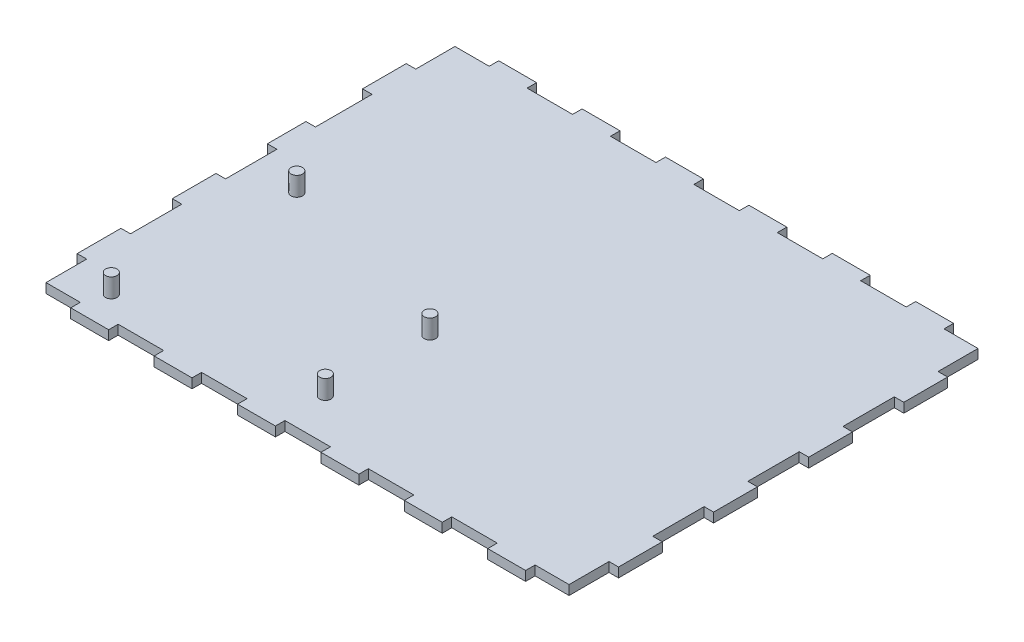
SolidWorks part; units mm, degrees
ref_plane "Front Plane" through (0, 0, 0) normal (0, 0, 1) x (1, 0, 0)
ref_plane "Top Plane" through (0, 0, 0) normal (0, 1, 0) x (1, 0, 0)
ref_plane "Right Plane" through (0, 0, 0) normal (1, 0, 0) x (0, 0, -1)
sketch "Sketch1" plane through (0, 0, 0) normal (0, 1, 0) x (1, 0, 0)
  line L1 (-72.39, 57.15) -> (72.39, 57.15)
  line L2 (-72.39, 57.15) -> (-72.39, -57.15)
  line L3 (-72.39, -57.15) -> (72.39, -57.15)
  line L4 (72.39, 57.15) -> (72.39, -57.15)
  line L5 (-72.39, 57.15) -> (72.39, -57.15) construction
  line L6 (-72.39, -57.15) -> (72.39, 57.15) construction
  point P0 (0, 0)
  dimension "D1" = 144.78
  dimension "D2" = 114.3
extrude "Boss-Extrude1" add sketch "Sketch1" along normal blind 63.5
sketch "Sketch2" plane through (0, 63.5, 0) normal (0, 1, 0) x (1, 0, 0)
  line L1 (-72.39, 57.15) -> (72.39, 57.15)
  line L2 (-72.39, 57.15) -> (-72.39, -57.15)
  line L3 (-72.39, -57.15) -> (72.39, -57.15)
  line L4 (72.39, 57.15) -> (72.39, -57.15)
  line L5 (-72.39, 57.15) -> (72.39, -57.15) construction
  line L6 (-72.39, -57.15) -> (72.39, 57.15) construction
  point P0 (0, 0)
extrude "Cut-Extrude1" cut sketch "Sketch2" against normal blind 60.96
sketch "Sketch3" plane through (0, 2.54, 0) normal (0, 1, 0) x (1, 0, 0)
  line L0 (-72.39, 57.15) -> (-72.39, -57.15) construction
  line L1 (-72.39, 2.2148) -> (-3.81, 2.2148) construction
  line L2 (-72.39, 2.2148) -> (-72.39, -51.1252) construction
  line L3 (-72.39, -51.1252) -> (-3.81, -51.1252) construction
  line L4 (-3.81, 2.2148) -> (-3.81, -51.1252) construction
  line L5 (-72.39, 2.2148) -> (-3.81, -51.1252) construction
  line L6 (-72.39, -51.1252) -> (-3.81, 2.2148) construction
  line L7 (-72.39, -57.15) -> (72.39, -57.15) construction
  circle A0 centre (-58.42, -48.5852) radius 1.524
  circle A1 centre (-6.35, -43.5052) radius 1.524
  circle A2 centre (-6.35, -15.5652) radius 1.524
  circle A3 centre (-57.15, -0.3252) radius 1.524
  point P0 (-3.6659, -1.4511)
  dimension "D10" = 3.048
  dimension "D1" = 68.58
  dimension "D2" = 53.34
  dimension "D3" = 2.54
  dimension "D4" = 5.08
  dimension "D5" = 27.94
  dimension "D6" = 15.24
  dimension "D7" = 1.27
  dimension "D8" = 13.97
  dimension "D9" = 50.8
  dimension "D11" = 6.0248
extrude "Boss-Extrude2" add sketch "Sketch3" along normal blind 5.08
sketch "Sketch4" plane through (0, 2.54, 0) normal (0, 1, 0) x (1, 0, 0)
  line L0 (69.85, 54.61) -> (61.2969, 54.61)
  line L1 (61.2969, 54.61) -> (61.2969, 57.15)
  line L2 (61.2969, 57.15) -> (50.16, 57.15)
  line L3 (50.16, 57.15) -> (50.16, 54.61)
  line L4 (50.16, 54.61) -> (39.023, 54.61)
  line L5 (39.023, 54.61) -> (39.023, 57.15)
  line L6 (39.023, 57.15) -> (27.8861, 57.15)
  line L7 (27.8861, 57.15) -> (27.8861, 54.61)
  line L8 (27.8861, 54.61) -> (16.7492, 54.61)
  line L9 (16.7492, 54.61) -> (16.7492, 57.15)
  line L10 (16.7492, 57.15) -> (5.6123, 57.15)
  line L11 (5.6123, 57.15) -> (5.6123, 54.61)
  line L12 (5.6123, 54.61) -> (-5.5247, 54.61)
  line L13 (-5.5247, 54.61) -> (-5.5247, 57.15)
  line L14 (-5.5247, 57.15) -> (-16.6616, 57.15)
  line L15 (-16.6616, 57.15) -> (-16.6616, 54.61)
  line L16 (-16.6616, 54.61) -> (-27.7985, 54.61)
  line L17 (-27.7985, 54.61) -> (-27.7985, 57.15)
  line L18 (-27.7985, 57.15) -> (-38.9354, 57.15)
  line L19 (-38.9354, 57.15) -> (-38.9354, 54.61)
  line L20 (-38.9354, 54.61) -> (-50.0724, 54.61)
  line L21 (-50.0724, 54.61) -> (-50.0724, 57.15)
  line L22 (-50.0724, 57.15) -> (-61.2093, 57.15)
  line L23 (-61.2093, 57.15) -> (-61.2093, 54.61)
  line L24 (-61.2093, 54.61) -> (-69.85, 54.61)
  line L25 (-61.2093, 54.61) -> (-61.2093, -57.15) construction
  line L26 (72.39, 57.15) -> (-72.39, 57.15) construction
  line L52 (-72.39, 57.15) -> (-72.39, -57.15) construction
  line L53 (5.6123, 54.61) -> (5.6123, -57.15) construction
  line L54 (-69.85, 54.61) -> (-69.85, 44.6536)
  line L55 (-69.85, 44.6536) -> (-72.39, 44.6536)
  line L56 (-72.39, 44.6536) -> (-72.39, 31.9536)
  line L57 (-72.39, 31.9536) -> (-69.85, 31.9536)
  line L58 (-69.85, 31.9536) -> (-69.85, 19.2536)
  line L59 (-69.85, 19.2536) -> (-72.39, 19.2536)
  line L60 (-72.39, 19.2536) -> (-72.39, 6.5536)
  line L61 (-72.39, 6.5536) -> (-69.85, 6.5536)
  line L62 (-69.85, 6.5536) -> (-69.85, -6.1464)
  line L63 (-69.85, -6.1464) -> (-72.39, -6.1464)
  line L64 (-72.39, -6.1464) -> (-72.39, -18.8464)
  line L65 (-72.39, -18.8464) -> (-69.85, -18.8464)
  line L66 (-69.85, -18.8464) -> (-69.85, -31.5464)
  line L67 (-69.85, -31.5464) -> (-72.39, -31.5464)
  line L68 (-72.39, -31.5464) -> (-72.39, -44.2464)
  line L69 (-72.39, -44.2464) -> (-69.85, -44.2464)
  line L70 (-69.85, -44.2464) -> (-69.85, -54.61)
  line L71 (69.85, 54.61) -> (69.85, 44.45)
  line L72 (69.85, 44.45) -> (72.39, 44.45)
  line L73 (72.39, 44.45) -> (72.39, 31.75)
  line L74 (72.39, 31.75) -> (69.85, 31.75)
  line L75 (69.85, 31.75) -> (69.85, 19.05)
  line L76 (69.85, 19.05) -> (72.39, 19.05)
  line L77 (72.39, 19.05) -> (72.39, 6.35)
  line L78 (72.39, 6.35) -> (69.85, 6.35)
  line L79 (69.85, 6.35) -> (69.85, -6.35)
  line L80 (69.85, -6.35) -> (72.39, -6.35)
  line L81 (72.39, -6.35) -> (72.39, -19.05)
  line L82 (72.39, -19.05) -> (69.85, -19.05)
  line L83 (69.85, -19.05) -> (69.85, -31.75)
  line L84 (69.85, -31.75) -> (72.39, -31.75)
  line L85 (72.39, -31.75) -> (72.39, -44.45)
  line L86 (72.39, -44.45) -> (69.85, -44.45)
  line L87 (69.85, -44.45) -> (69.85, -54.61)
  line L88 (61.2969, 54.61) -> (61.2969, -57.15) construction
  line L89 (72.39, -57.15) -> (72.39, 57.15) construction
  line L90 (-50.0724, 54.61) -> (-50.0724, -57.15) construction
  line L91 (-72.39, -57.15) -> (72.39, -57.15) construction
  line L92 (-38.9354, 54.61) -> (-38.9354, -57.15) construction
  line L93 (-27.7985, 54.61) -> (-27.7985, -57.15) construction
  line L94 (-16.6616, 54.61) -> (-16.6616, -57.15) construction
  line L95 (-5.5247, 54.61) -> (-5.5247, -57.15) construction
  line L96 (16.7492, 54.61) -> (16.7492, -57.15) construction
  line L97 (27.8861, 54.61) -> (27.8861, -57.15) construction
  line L98 (39.023, 54.61) -> (39.023, -57.15) construction
  line L99 (50.16, 54.61) -> (50.16, -57.15) construction
  line L100 (-69.85, -54.61) -> (-61.2093, -54.61)
  line L101 (-61.2093, -54.61) -> (-61.2093, -57.15)
  line L102 (-50.0724, -57.15) -> (-50.0724, -54.61)
  line L103 (-50.0724, -54.61) -> (-38.9354, -54.61)
  line L104 (-38.9354, -54.61) -> (-38.9354, -57.15)
  line L105 (-27.7985, -57.15) -> (-27.7985, -54.61)
  line L106 (-27.7985, -54.61) -> (-16.6616, -54.61)
  line L107 (-16.6616, -54.61) -> (-16.6616, -57.15)
  line L108 (-5.5247, -57.15) -> (-5.5247, -54.61)
  line L109 (-5.5247, -54.61) -> (5.6123, -54.61)
  line L110 (5.6123, -54.61) -> (5.6123, -57.15)
  line L111 (16.7492, -57.15) -> (16.7492, -54.61)
  line L112 (16.7492, -54.61) -> (27.8861, -54.61)
  line L113 (27.8861, -54.61) -> (27.8861, -57.15)
  line L114 (39.023, -57.15) -> (39.023, -54.61)
  line L115 (39.023, -54.61) -> (50.16, -54.61)
  line L116 (50.16, -54.61) -> (50.16, -57.15)
  line L117 (61.2969, -57.15) -> (61.2969, -54.61)
  line L118 (61.2969, -54.61) -> (69.85, -54.61)
  line L119 (-61.2093, -57.15) -> (-50.0724, -57.15)
  line L120 (-38.9354, -57.15) -> (-27.7985, -57.15)
  line L121 (-16.6616, -57.15) -> (-5.5247, -57.15)
  line L122 (5.6123, -57.15) -> (16.7492, -57.15)
  line L123 (27.8861, -57.15) -> (39.023, -57.15)
  line L124 (61.2969, -57.15) -> (50.16, -57.15)
  dimension "D1" = 2.54
  dimension "D3" = 2.54
  dimension "D4" = 2.54
extrude "Cut-Extrude2" cut sketch "Sketch4" against normal blind 2.54 flip side to cut
sketch "Sketch6" plane through (0, 2.54, 0) normal (0, 1, 0) x (1, 0, 0)
  line L0 (-69.85, 54.61) -> (-60.7013, 54.61)
  line L2 (-60.7013, 54.61) -> (-60.7013, 57.15)
  line L3 (-50.0724, 57.15) -> (-61.2093, 57.15) construction
  line L4 (-69.85, 54.61) -> (-69.85, 44.1456)
  line L5 (-69.85, 44.1456) -> (-72.39, 44.1456)
  line L6 (-72.39, 44.6536) -> (-72.39, 31.9536) construction
  line L7 (-72.39, 44.1456) -> (-72.39, 32.4616)
  line L8 (-72.39, 32.4616) -> (-69.85, 32.4616)
  line L9 (-69.85, 32.4616) -> (-69.85, 17.3578)
  line L10 (-69.85, 17.3578) -> (-72.39, 17.3578)
  line L11 (-72.39, 19.2536) -> (-72.39, 6.5536) construction
  line L12 (-72.39, 17.3578) -> (-72.39, 7.0616)
  line L13 (-72.39, 7.0616) -> (-69.85, 7.0616)
  line L14 (-69.85, 7.0616) -> (-69.85, -6.6544)
  line L15 (-69.85, -6.6544) -> (-72.39, -6.6544)
  line L16 (-72.39, -6.1464) -> (-72.39, -18.8464) construction
  line L17 (-72.39, -6.6544) -> (-72.39, -18.3384)
  line L18 (-72.39, -18.3384) -> (-69.85, -18.3384)
  line L19 (-69.85, -18.3384) -> (-69.85, -32.0544)
  line L20 (-69.85, -32.0544) -> (-72.39, -32.0544)
  line L21 (-72.39, -31.5464) -> (-72.39, -44.2464) construction
  line L22 (-72.39, -32.0544) -> (-72.39, -43.7384)
  line L23 (-72.39, -43.7384) -> (-69.85, -43.7384)
  line L24 (-69.85, -43.7384) -> (-69.85, -54.61)
  line L25 (-69.85, -44.2464) -> (-69.85, -54.61) construction
  line L27 (-72.39, 44.6536) -> (-72.39, 44.1456) construction
  line L28 (-72.39, 31.9536) -> (-72.39, 32.4616) construction
  line L29 (-72.39, 17.3578) -> (-72.39, 17.8658) construction
  line L30 (-72.39, 7.0616) -> (-72.39, 6.5536) construction
  line L31 (-72.39, -6.1464) -> (-72.39, -6.6544) construction
  line L32 (-72.39, -18.8464) -> (-72.39, -18.3384) construction
  line L33 (-72.39, -18.8464) -> (-69.85, -18.8464) construction
  line L34 (-72.39, -32.0544) -> (-72.39, -31.5464) construction
  line L35 (-72.39, -44.2464) -> (-72.39, -43.7384) construction
  line L36 (-60.7013, 57.15) -> (-50.5804, 57.15)
  line L37 (-50.5804, 57.15) -> (-50.5804, 54.61)
  line L38 (-50.5804, 54.61) -> (-38.4274, 54.61)
  line L39 (-38.4274, 54.61) -> (-38.4274, 57.15)
  line L40 (-27.7985, 57.15) -> (-38.9354, 57.15) construction
  line L41 (-38.4274, 57.15) -> (-28.3065, 57.15)
  line L42 (-28.3065, 57.15) -> (-28.3065, 54.61)
  line L43 (-28.3065, 54.61) -> (-16.1536, 54.61)
  line L44 (-16.1536, 54.61) -> (-16.1536, 57.15)
  line L45 (-5.5247, 57.15) -> (-16.6616, 57.15) construction
  line L46 (-16.1536, 57.15) -> (-6.0327, 57.15)
  line L47 (-6.0327, 57.15) -> (-6.0327, 54.61)
  line L48 (-6.0327, 54.61) -> (6.1203, 54.61)
  line L49 (6.1203, 54.61) -> (6.1203, 57.15)
  line L50 (6.1203, 57.15) -> (16.2412, 57.15)
  line L51 (16.7492, 57.15) -> (5.6123, 57.15) construction
  line L52 (16.2412, 57.15) -> (16.2412, 54.61)
  line L53 (16.2412, 54.61) -> (28.3941, 54.61)
  line L54 (28.3941, 54.61) -> (28.3941, 57.15)
  line L55 (39.023, 57.15) -> (27.8861, 57.15) construction
  line L56 (28.3941, 57.15) -> (38.515, 57.15)
  line L57 (38.515, 57.15) -> (38.515, 54.61)
  line L58 (38.515, 54.61) -> (50.668, 54.61)
  line L59 (50.668, 54.61) -> (50.668, 57.15)
  line L60 (61.2969, 57.15) -> (50.16, 57.15) construction
  line L61 (50.668, 57.15) -> (60.7889, 57.15)
  line L62 (60.7889, 57.15) -> (60.7889, 54.61)
  line L63 (60.7889, 54.61) -> (69.85, 54.61)
  line L64 (69.85, 54.61) -> (69.85, 43.942)
  line L65 (69.85, 43.942) -> (72.39, 43.942)
  line L66 (72.39, 31.75) -> (72.39, 44.45) construction
  line L67 (72.39, 43.942) -> (72.39, 32.258)
  line L68 (72.39, 32.258) -> (69.85, 32.258)
  line L69 (69.85, 32.258) -> (69.85, 18.542)
  line L70 (69.85, 18.542) -> (72.39, 18.542)
  line L71 (72.39, 6.35) -> (72.39, 19.05) construction
  line L72 (72.39, 18.542) -> (72.39, 6.858)
  line L73 (72.39, 6.858) -> (69.85, 6.858)
  line L74 (69.85, 6.858) -> (69.85, -6.858)
  line L75 (69.85, -6.858) -> (72.39, -6.858)
  line L76 (72.39, -19.05) -> (72.39, -6.35) construction
  line L77 (72.39, -6.858) -> (72.39, -18.542)
  line L78 (72.39, -18.542) -> (69.85, -18.542)
  line L79 (69.85, -18.542) -> (69.85, -32.258)
  line L80 (69.85, -32.258) -> (72.39, -32.258)
  line L81 (72.39, -44.45) -> (72.39, -31.75) construction
  line L82 (72.39, -32.258) -> (72.39, -43.942)
  line L83 (72.39, -43.942) -> (69.85, -43.942)
  line L84 (69.85, -43.942) -> (69.85, -54.61)
  line L85 (69.85, -54.61) -> (60.7889, -54.61)
  line L86 (60.7889, -54.61) -> (60.7889, -57.15)
  line L87 (50.16, -57.15) -> (61.2969, -57.15) construction
  line L88 (60.7889, -57.15) -> (50.668, -57.15)
  line L89 (50.668, -57.15) -> (50.668, -54.61)
  line L90 (50.668, -54.61) -> (38.515, -54.61)
  line L91 (38.515, -54.61) -> (38.515, -57.15)
  line L92 (27.8861, -57.15) -> (39.023, -57.15) construction
  line L93 (38.515, -57.15) -> (28.3941, -57.15)
  line L94 (28.3941, -57.15) -> (28.3941, -54.61)
  line L95 (28.3941, -54.61) -> (16.2412, -54.61)
  line L96 (16.2412, -54.61) -> (16.2412, -57.15)
  line L97 (5.6123, -57.15) -> (16.7492, -57.15) construction
  line L98 (16.2412, -57.15) -> (6.1203, -57.15)
  line L99 (6.1203, -57.15) -> (6.1203, -54.61)
  line L100 (6.1203, -54.61) -> (-6.0327, -54.61)
  line L101 (-6.0327, -54.61) -> (-6.0327, -57.15)
  line L102 (-16.6616, -57.15) -> (-5.5247, -57.15) construction
  line L103 (-6.0327, -57.15) -> (-16.1536, -57.15)
  line L104 (-16.1536, -57.15) -> (-16.1536, -54.61)
  line L105 (-16.1536, -54.61) -> (-28.3065, -54.61)
  line L106 (-28.3065, -54.61) -> (-28.3065, -57.15)
  line L107 (-38.9354, -57.15) -> (-27.7985, -57.15) construction
  line L108 (-28.3065, -57.15) -> (-38.4274, -57.15)
  line L109 (-38.4274, -57.15) -> (-38.4274, -54.61)
  line L110 (-38.4274, -54.61) -> (-50.5804, -54.61)
  line L111 (-50.5804, -54.61) -> (-50.5804, -57.15)
  line L112 (-61.2093, -57.15) -> (-50.0724, -57.15) construction
  line L113 (-50.5804, -57.15) -> (-60.7013, -57.15)
  line L114 (-60.7013, -57.15) -> (-60.7013, -54.61)
  line L115 (-60.7013, -54.61) -> (-69.85, -54.61)
  line L116 (-61.2093, -57.15) -> (-60.7013, -57.15) construction
  line L117 (-50.0724, -57.15) -> (-50.5804, -57.15) construction
  line L118 (-38.9354, -57.15) -> (-38.4274, -57.15) construction
  line L119 (-27.7985, -57.15) -> (-28.3065, -57.15) construction
  line L120 (-16.6616, -57.15) -> (-16.1536, -57.15) construction
  line L121 (-5.5247, -57.15) -> (-6.0327, -57.15) construction
  line L122 (5.6123, -57.15) -> (6.1203, -57.15) construction
  line L123 (16.7492, -57.15) -> (16.2412, -57.15) construction
  line L124 (27.8861, -57.15) -> (28.3941, -57.15) construction
  line L125 (39.023, -57.15) -> (38.515, -57.15) construction
  line L126 (50.16, -57.15) -> (50.668, -57.15) construction
  line L127 (61.2969, -57.15) -> (60.7889, -57.15) construction
  line L128 (72.39, -44.45) -> (72.39, -43.942) construction
  line L129 (72.39, -31.75) -> (72.39, -32.258) construction
  line L130 (72.39, -19.05) -> (72.39, -18.542) construction
  line L131 (72.39, -6.35) -> (72.39, -6.858) construction
  line L132 (72.39, 6.35) -> (72.39, 6.858) construction
  line L133 (72.39, 19.05) -> (72.39, 18.542) construction
  line L134 (72.39, 31.75) -> (72.39, 32.258) construction
  line L135 (72.39, 44.45) -> (72.39, 43.942) construction
  line L136 (61.2969, 57.15) -> (60.7889, 57.15) construction
  line L137 (50.16, 57.15) -> (50.668, 57.15) construction
  line L138 (39.023, 57.15) -> (38.515, 57.15) construction
  line L139 (27.8861, 57.15) -> (28.3941, 57.15) construction
  line L140 (16.7492, 57.15) -> (16.2412, 57.15) construction
  line L141 (5.6123, 57.15) -> (6.1203, 57.15) construction
  line L142 (-5.5247, 57.15) -> (-6.0327, 57.15) construction
  line L143 (-16.6616, 57.15) -> (-16.1536, 57.15) construction
  line L144 (-27.7985, 57.15) -> (-28.3065, 57.15) construction
  line L145 (-38.9354, 57.15) -> (-38.4274, 57.15) construction
  line L146 (-50.0724, 57.15) -> (-50.5804, 57.15) construction
  line L147 (-61.2093, 57.15) -> (-60.7013, 57.15) construction
  dimension "D1" = 0.508
extrude "Cut-Extrude4" cut sketch "Sketch6" against normal blind 2.54 flip side to cut
equation "\"5l7\"=2.48651"
